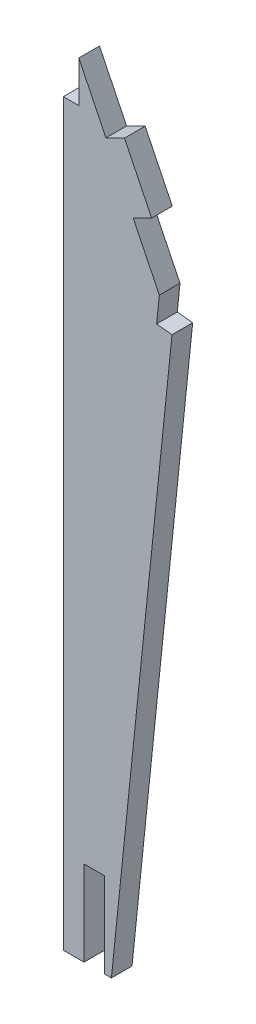
SolidWorks part; units mm, degrees
ref_plane "前视基准面" through (0, 0, 0) normal (0, 0, 1) x (1, 0, 0)
ref_plane "上视基准面" through (0, 0, 0) normal (0, 1, 0) x (1, 0, 0)
ref_plane "右视基准面" through (0, 0, 0) normal (1, 0, 0) x (0, 0, -1)
sketch "草图1" plane through (0, 0, 0) normal (0, 0, 1) x (1, 0, 0)
  line L0 (10.9578, 79.75) -> (10.9578, 75.75)
  line L1 (10.9578, 75.75) -> (9.4578, 75.75)
  line L2 (9.4578, 75.75) -> (9.4578, 4.1273)
  line L3 (10.9578, 79.75) -> (13.588, 74.3572)
  line L4 (13.588, 74.3572) -> (15.3856, 75.234)
  line L5 (15.3856, 75.234) -> (18.0158, 69.8412)
  line L6 (18.0158, 69.8412) -> (16.2182, 68.9645)
  line L7 (16.2182, 68.9645) -> (18.7612, 63.7506)
  line L8 (9.4578, 4.1273) -> (11.4578, 4.1273)
  line L9 (11.4578, 4.1273) -> (11.4578, 12.3773)
  line L10 (11.4578, 12.3773) -> (13.4578, 12.3773)
  line L11 (19.9897, 61.0436) -> (14.1141, 4.1273)
  line L12 (13.4578, 12.3773) -> (13.4578, 4.1273)
  line L13 (13.4578, 4.1273) -> (14.1141, 4.1273)
  line L14 (18.7612, 63.7506) -> (18.4976, 61.1976)
  line L15 (18.4976, 61.1976) -> (19.9897, 61.0436)
  line L16 (18.7612, 63.7506) -> (18.4976, 61.1976)
  line L17 (18.4976, 61.1976) -> (19.9897, 61.0436)
extrude "凸台-拉伸1" add sketch "草图1" along normal blind 2 contours L15 L14 L7 L6 L5 L4 L3 L0 L1 L2 L8 L9 L10 L12 L13 L11
